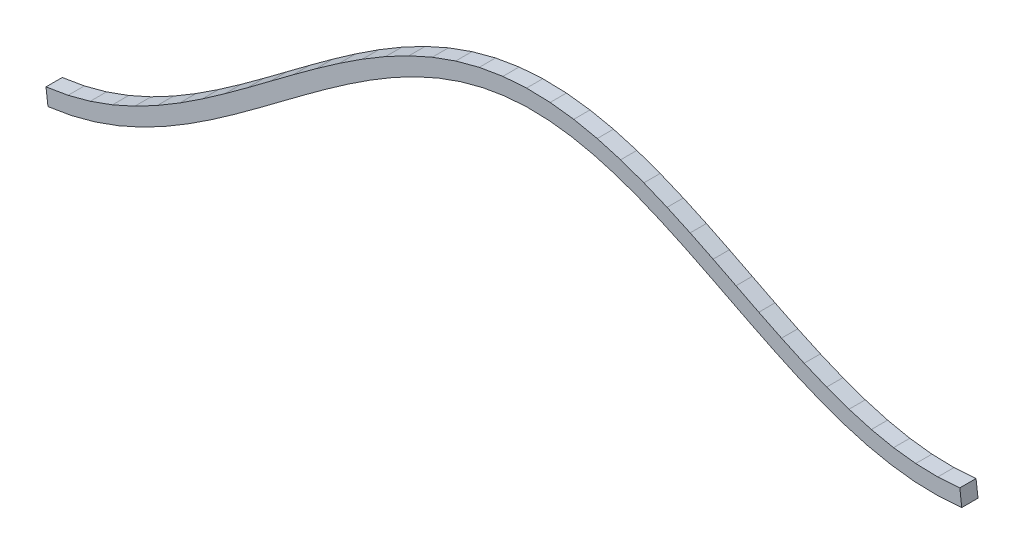
SolidWorks part; units mm, degrees
ref_plane "前视基准面" through (0, 0, 0) normal (0, 0, 1) x (1, 0, 0)
ref_plane "上视基准面" through (0, 0, 0) normal (0, 1, 0) x (1, 0, 0)
ref_plane "右视基准面" through (0, 0, 0) normal (1, 0, 0) x (0, 0, -1)
other "Configuration Table"
sketch "草图1" plane through (0, 0, 0) normal (0, 0, 1) x (1, 0, 0)
  line L0 (0.2382, -1.9858) -> (6.0527, -1.002)
  line L1 (6.0527, -1.002) -> (11.8518, 0.5431)
  line L2 (11.8518, 0.5431) -> (17.6298, 2.6237)
  line L3 (17.6298, 2.6237) -> (23.3839, 5.2006)
  line L4 (23.3839, 5.2006) -> (29.114, 8.2232)
  line L5 (29.114, 8.2232) -> (34.8214, 11.6313)
  line L6 (34.8214, 11.6313) -> (40.508, 15.3561)
  line L7 (40.508, 15.3561) -> (46.1758, 19.3221)
  line L8 (46.1758, 19.3221) -> (51.8264, 23.4479)
  line L9 (51.8264, 23.4479) -> (57.4606, 27.6486)
  line L10 (57.4606, 27.6486) -> (63.0789, 31.8374)
  line L11 (63.0789, 31.8374) -> (68.6808, 35.9278)
  line L12 (68.6808, 35.9278) -> (74.2655, 39.8357)
  line L13 (74.2655, 39.8357) -> (79.8314, 43.4816)
  line L14 (79.8314, 43.4816) -> (85.3765, 46.793)
  line L15 (85.3765, 46.793) -> (90.8989, 49.7063)
  line L16 (90.8989, 49.7063) -> (96.3973, 52.169)
  line L17 (96.3973, 52.169) -> (101.8718, 54.1407)
  line L18 (101.8718, 54.1407) -> (107.3252, 55.594)
  line L19 (107.3252, 55.594) -> (112.7632, 56.5142)
  line L20 (112.7632, 56.5142) -> (118.1946, 56.8985)
  line L21 (118.1946, 56.8985) -> (123.6296, 56.7542)
  line L22 (123.6296, 56.7542) -> (129.0777, 56.0994)
  line L23 (129.0777, 56.0994) -> (134.5463, 54.9623)
  line L24 (134.5463, 54.9623) -> (140.0394, 53.3824)
  line L25 (140.0394, 53.3824) -> (145.5587, 51.4107)
  line L26 (145.5587, 51.4107) -> (151.1037, 49.109)
  line L27 (151.1037, 49.109) -> (156.6733, 46.5481)
  line L28 (156.6733, 46.5481) -> (162.2661, 43.8063)
  line L29 (162.2661, 43.8063) -> (167.8814, 40.967)
  line L30 (167.8814, 40.967) -> (173.5186, 38.1167)
  line L31 (173.5186, 38.1167) -> (179.1783, 35.3423)
  line L32 (179.1783, 35.3423) -> (184.8612, 32.7294)
  line L33 (184.8612, 32.7294) -> (190.5687, 30.3604)
  line L34 (190.5687, 30.3604) -> (196.3019, 28.3126)
  line L35 (196.3019, 28.3126) -> (202.0613, 26.6565)
  line L36 (202.0613, 26.6565) -> (207.8452, 25.4541)
  line L37 (207.8452, 25.4541) -> (213.6496, 24.7567)
  line L38 (213.6496, 24.7567) -> (219.4671, 24.6025)
  line L39 (219.4671, 24.6025) -> (225.2882, 25.0142)
  line L40 (225.2882, 25.0142) -> (224.8118, 28.9858)
  line L41 (224.8118, 28.9858) -> (219.3804, 28.6015)
  line L42 (219.3804, 28.6015) -> (213.9454, 28.7458)
  line L43 (213.9454, 28.7458) -> (208.4973, 29.4006)
  line L44 (208.4973, 29.4006) -> (203.0287, 30.5377)
  line L45 (203.0287, 30.5377) -> (197.5356, 32.1176)
  line L46 (197.5356, 32.1176) -> (192.0163, 34.0893)
  line L47 (192.0163, 34.0893) -> (186.4713, 36.391)
  line L48 (186.4713, 36.391) -> (180.9017, 38.9519)
  line L49 (180.9017, 38.9519) -> (175.3089, 41.6937)
  line L50 (175.3089, 41.6937) -> (169.6936, 44.533)
  line L51 (169.6936, 44.533) -> (164.0564, 47.3833)
  line L52 (164.0564, 47.3833) -> (158.3967, 50.1577)
  line L53 (158.3967, 50.1577) -> (152.7138, 52.7706)
  line L54 (152.7138, 52.7706) -> (147.0063, 55.1396)
  line L55 (147.0063, 55.1396) -> (141.2731, 57.1874)
  line L56 (141.2731, 57.1874) -> (135.5137, 58.8435)
  line L57 (135.5137, 58.8435) -> (129.7298, 60.0459)
  line L58 (129.7298, 60.0459) -> (123.9254, 60.7433)
  line L59 (123.9254, 60.7433) -> (118.1079, 60.8975)
  line L60 (118.1079, 60.8975) -> (112.2868, 60.4858)
  line L61 (112.2868, 60.4858) -> (106.4723, 59.502)
  line L62 (106.4723, 59.502) -> (100.6732, 57.9569)
  line L63 (100.6732, 57.9569) -> (94.8952, 55.8763)
  line L64 (94.8952, 55.8763) -> (89.1411, 53.2994)
  line L65 (89.1411, 53.2994) -> (83.411, 50.2768)
  line L66 (83.411, 50.2768) -> (77.7036, 46.8687)
  line L67 (77.7036, 46.8687) -> (72.017, 43.1439)
  line L68 (72.017, 43.1439) -> (66.3492, 39.1779)
  line L69 (66.3492, 39.1779) -> (60.6986, 35.0521)
  line L70 (60.6986, 35.0521) -> (55.0644, 30.8514)
  line L71 (55.0644, 30.8514) -> (49.4461, 26.6626)
  line L72 (49.4461, 26.6626) -> (43.8442, 22.5722)
  line L73 (43.8442, 22.5722) -> (38.2595, 18.6643)
  line L74 (38.2595, 18.6643) -> (32.6936, 15.0184)
  line L75 (32.6936, 15.0184) -> (27.1485, 11.707)
  line L76 (27.1485, 11.707) -> (21.6261, 8.7937)
  line L77 (21.6261, 8.7937) -> (16.1277, 6.331)
  line L78 (16.1277, 6.331) -> (10.6532, 4.3593)
  line L79 (10.6532, 4.3593) -> (5.1998, 2.906)
  line L80 (5.1998, 2.906) -> (-0.2382, 1.9858)
  line L81 (-0.2382, 1.9858) -> (0.2382, -1.9858)
extrude "Service_Bow" add sketch "草图1" along normal blind 4
